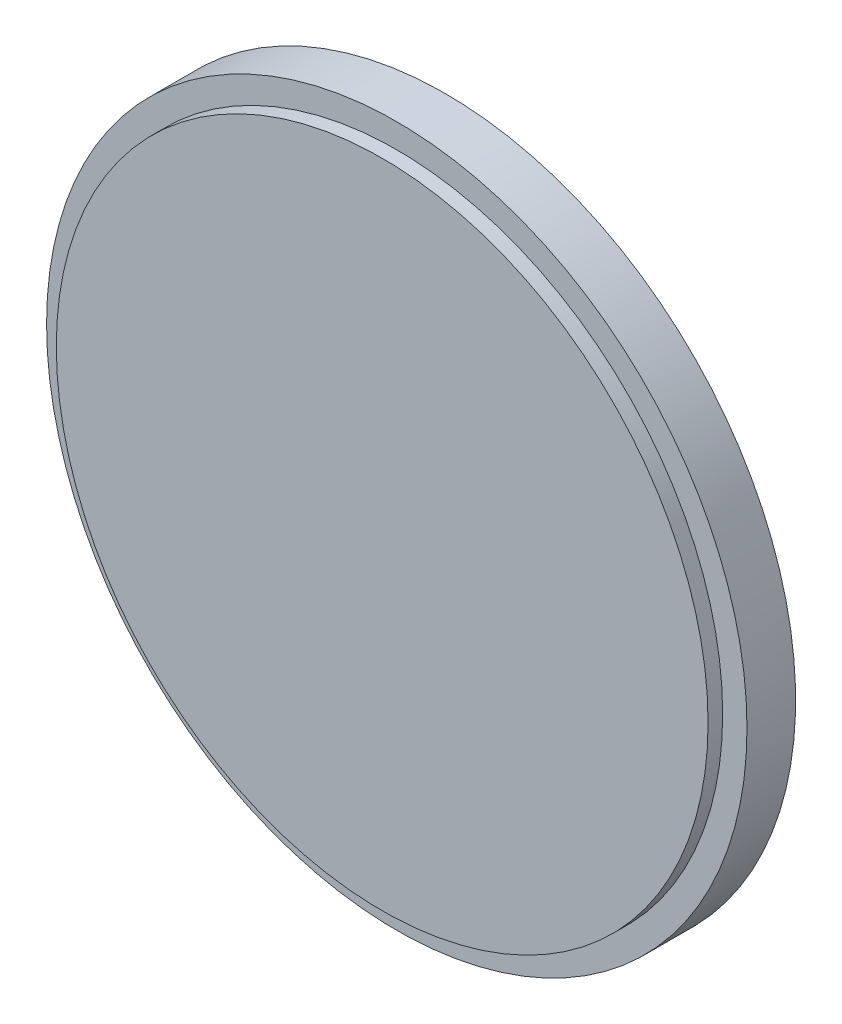
SolidWorks part; units mm, degrees
material "Liga 1060"
ref_plane "Plano frontal" through (0, 0, 0) normal (0, 0, 1) x (1, 0, 0)
ref_plane "Plano superior" through (0, 0, 0) normal (0, 1, 0) x (1, 0, 0)
ref_plane "Plano direito" through (0, 0, 0) normal (1, 0, 0) x (0, 0, -1)
sketch "Esboço1" plane through (0, 0, 0) normal (0, 0, 1) x (1, 0, 0)
  circle A0 centre (0, 0) radius 32.5
  circle A1 centre (0, 0) radius 35
extrude "Ressalto-extrusão1" add sketch "Esboço1" along normal blind 8
sketch "Esboço2" plane through (0, 0, 8) normal (0, 0, 1) x (1, 0, 0)
  circle A0 centre (0, 0) radius 32.5
extrude "Ressalto-extrusão2" add sketch "Esboço2" against normal blind 3
sketch "Esboço3" plane through (0, 0, 8) normal (0, 0, 1) x (1, 0, 0)
  circle A0 centre (0, 0) radius 2.5
extrude "Corte-extrusão1" cut sketch "Esboço3" against normal blind 3
sketch "Esboço4" plane through (0, 0, 5) normal (0, 0, -1) x (-1, 0, 0)
  circle A0 centre (0, 0) radius 37
  circle A1 centre (0, 0) radius 35
extrude "Ressalto-extrusão3" add sketch "Esboço4" against normal through all and the other way through all
sketch "Esboço5" plane through (0, 0, 0) normal (0, 1, 0) x (1, 0, 0)
  line L0 (-37, -1) -> (-37, -7)
  line L1 (-37, -4) -> (-13.2615, -4)
  line L2 (-35.2, -4) -> (-35.2, -1)
  line L3 (-35.2, -1) -> (-37, -1)
  line L4 (-35.2, -4) -> (-35.2, -7)
  line L5 (-35.2, -7) -> (-37, -7)
revolve "Corte-Revolução1" cut sketch "Esboço5" angle 360 about axis through (0, 0, 8) along (0, 0, -1)
sketch "Esboço6" plane through (0, 0, 5) normal (0, 0, -1) x (-1, 0, 0)
  circle A0 centre (0, 0) radius 12.55
  dimension "D1" = 25.1
extrude "Ressalto-extrusão4" add sketch "Esboço6" along normal blind 5
sketch "Esboço7" plane through (0, 0, 0) normal (0, 0, -1) x (-1, 0, 0)
  circle A0 centre (0, 0) radius 7.55
  dimension "D1" = 15.1
extrude "Corte-extrusão2" cut sketch "Esboço7" against normal through all both and the other way through all
sketch "Esboço8" plane through (0, 0, 8) normal (0, 0, 1) x (1, 0, 0)
  circle A0 centre (0, 0) radius 37
  circle A1 centre (0, 0) radius 32.5
  dimension "D1" = 74
extrude "Ressalto-extrusão5" add sketch "Esboço8" against normal up to surface (8 mm away) up to face at (32.5, 0, 0)
sketch "Esboço9" plane through (0, 0, 8) normal (0, 0, 1) x (1, 0, 0)
  circle A0 centre (0, 0) radius 37
  circle A1 centre (0, 0) radius 33.5
extrude "Corte-extrusão8" cut sketch "Esboço9" against normal blind 1.5
sketch "Esboço12" plane through (0, 0, 0) normal (0, 0, -1) x (-1, 0, 0)
  circle A0 centre (0, 0) radius 37
  circle A1 centre (0, 0) radius 33.5
  dimension "D1" = 74
extrude "Corte-extrusão9" cut sketch "Esboço12" against normal blind 1.5
sketch "Esboço13" plane through (0, 0, 1.5) normal (0, 0, -1) x (-1, 0, 0)
  circle A1 centre (0, 0) radius 36
  circle A2 centre (0, 0) radius 37
extrude "Corte-extrusão10" cut sketch "Esboço13" against normal blind 10
sketch "Esboço14" plane through (0, 0, 6.5) normal (0, 0, 1) x (1, 0, 0)
  circle A0 centre (0, 0) radius 37
  circle A1 centre (0, 0) radius 36
  circle A3 centre (0, 0) radius 36
  circle A6 centre (0, 0) radius 36
  circle M3 centre (0, 0) radius 36
  dimension "D1" = 0
extrude "Ressalto-extrusão6" add sketch "Esboço14" against normal up to surface (5 mm away) contours A0 M3 up to face at (-33.5, 0, 1.5)
sketch "Esboço15" plane through (0, 0, 0) normal (0, 0, -1) x (-1, 0, 0)
  circle A0 centre (0, 0) radius 12.55
extrude "Corte-extrusão11" cut sketch "Esboço15" against normal through all
sketch "Esboço16" plane through (0, 0, 5) normal (0, 0, -1) x (-1, 0, 0)
  circle A0 centre (0, 0) radius 12.55 construction
  circle A1 centre (0, 0) radius 12.55
extrude "Ressalto-extrusão7" add sketch "Esboço16" against normal through all
sketch "Esboço17" plane through (0, 0, 5) normal (0, 0, -1) x (-1, 0, 0)
  circle A0 centre (0, 0) radius 10
  dimension "D1" = 20
extrude "Ressalto-extrusão8" add sketch "Esboço17" along normal blind 16
sketch "Esboço18" plane through (0, 0, -11) normal (0, 0, -1) x (-1, 0, 0)
  circle A0 centre (0, 0) radius 3.3
  dimension "D1" = 6.6
extrude "Corte-extrusão12" cut sketch "Esboço18" against normal blind 16
sketch "Esboço19" plane through (0, 0, -11) normal (0, 0, -1) x (-1, 0, 0)
  line L0 (0, -3.3) -> (0, -5.3) construction
  line L1 (-2.975, -5.3) -> (2.975, -5.3)
  line L2 (2.975, -5.3) -> (2.975, -7.95)
  line L3 (2.975, -7.95) -> (-2.975, -7.95)
  line L4 (-2.975, -7.95) -> (-2.975, -5.3)
  line L5 (-3.3, 0) -> (3.3, 0) construction
  line L6 (-2.975, 7.95) -> (-2.975, 5.3)
  line L7 (2.975, 7.95) -> (-2.975, 7.95)
  line L8 (2.975, 5.3) -> (2.975, 7.95)
  line L9 (-2.975, 5.3) -> (2.975, 5.3)
  circle A1 centre (0, 0) radius 3.3 construction
  circle A2 centre (0, 0) radius 3.3 construction
  point P12 (0, -5.3)
  point P19 (0, 5.3)
  dimension "D1" = 2
  dimension "D2" = 5.95
  dimension "D3" = 2.65
extrude "Corte-extrusão13" cut sketch "Esboço19" against normal blind 8
sketch "Esboço21" plane through (0, 5.3, 0) normal (0, 1, 0) x (1, 0, 0)
  line L0 (0, 11) -> (0, 8.5) construction
  line L1 (-2.975, 11) -> (2.975, 11) construction
  circle A0 centre (0, 6.85) radius 1.65
  dimension "D2" = 3.3
  dimension "D1" = 2.5
extrude "Corte-extrusão14" cut sketch "Esboço21" against normal through all both and the other way through all
sketch "Esboço23" plane through (0, 0, 1.5) normal (0, 0, -1) x (-1, 0, 0)
  circle A0 centre (0, 0) radius 36
  circle A1 centre (0, 0) radius 37 construction
  circle A2 centre (0, 0) radius 37
  dimension "D1" = 72
extrude "Corte-extrusão15" cut sketch "Esboço23" against normal through all
